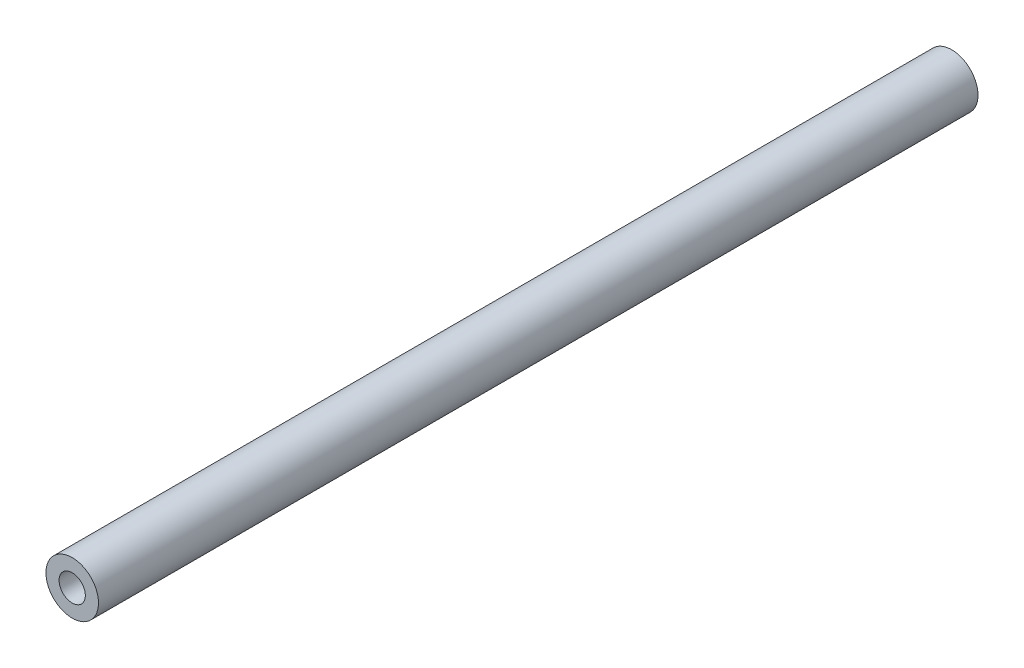
SolidWorks part; units mm, degrees
ref_plane "Front" through (0, 0, 0) normal (0, 0, 1) x (1, 0, 0)
ref_plane "Top" through (0, 0, 0) normal (0, 1, 0) x (1, 0, 0)
ref_plane "Right" through (0, 0, 0) normal (1, 0, 0) x (0, 0, -1)
sketch "Sketch1" plane through (0, 0, 0) normal (0, 0, 1) x (1, 0, 0)
  circle A1 centre (0, 0) radius 4
  dimension "D1" = 8
extrude "Extrude1" add sketch "Sketch1" along normal blind 134
sketch "Sketch2" plane through (0, 0, 134) normal (0, 0, 1) x (1, 0, 0)
  circle A0 centre (0, 0) radius 2
  dimension "D1" = 4
extrude "Extrude2" cut sketch "Sketch2" against normal blind 10
sketch "Sketch3" plane through (0, 0, 0) normal (0, 0, -1) x (-1, 0, 0)
  circle A0 centre (0, 0) radius 2
  dimension "D1" = 4
extrude "Extrude3" cut sketch "Sketch3" against normal blind 10
